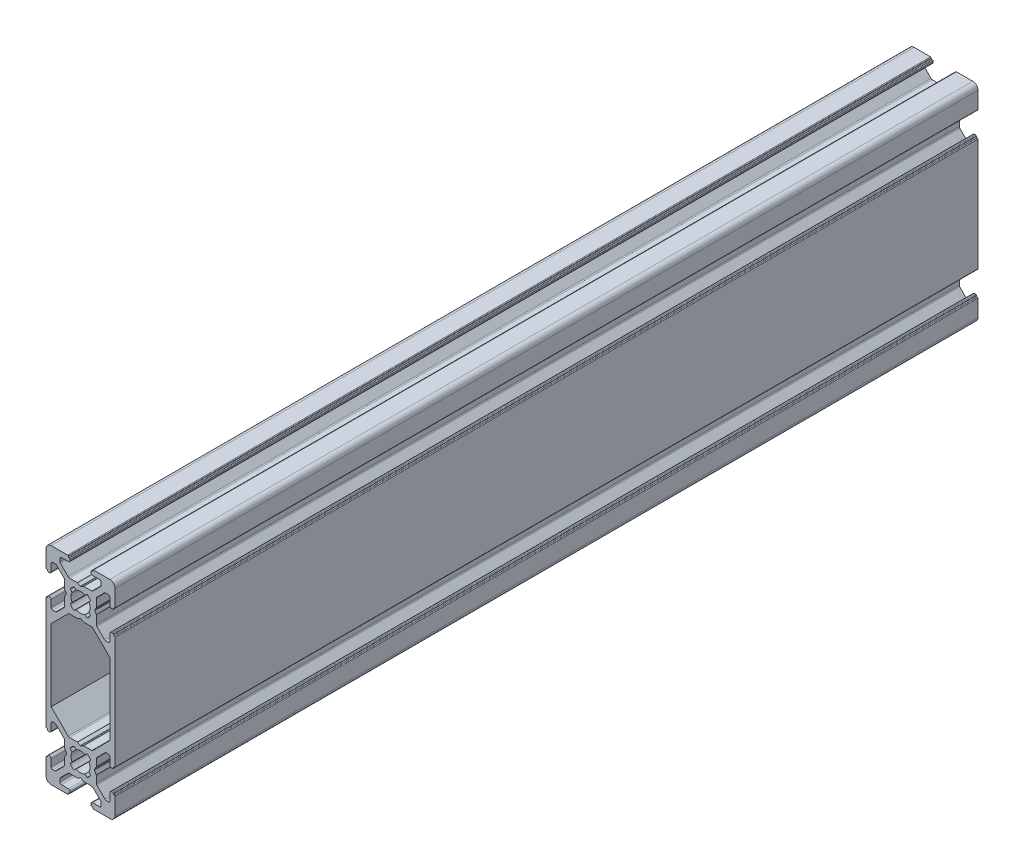
SolidWorks part; units mm, degrees
ref_plane "Front Plane" through (0, 0, 0) normal (0, 0, 1) x (1, 0, 0)
ref_plane "Top Plane" through (0, 0, 0) normal (0, 1, 0) x (1, 0, 0)
ref_plane "Right Plane" through (0, 0, 0) normal (1, 0, 0) x (0, 0, -1)
sketch "Sketch2" plane through (0, 0, 0) normal (0, 0, 1) x (1, 0, 0)
  line L0 (0, -19.2121) -> (0, 56.5718) construction
  line L1 (-10, 36.2558) -> (-10, 8.5)
  line L2 (10, 36.2558) -> (10, 8.5)
  line L3 (-8.5, 30.4451) -> (-8.5, 9.5607)
  line L4 (8.5, 30.4451) -> (8.5, 9.5607)
  line L5 (-3.5858, 4.6464) -> (-8.5, 9.5607)
  line L6 (-4.7214, 3.4608) -> (-7.1142, 5.8536)
  line L7 (-3.75, -10) -> (-8.5, -10)
  line L8 (-4.7214, -3.4608) -> (-7.1142, -5.8536)
  line L9 (-9.7, -3.55) -> (-9.8, -3.55)
  line L10 (-9.5, -3.2) -> (-9.5, -3.35)
  line L11 (-7.4678, -6) -> (-8, -6)
  line L12 (-9, -3) -> (-9.3, -3)
  line L13 (-8.5, -3.5) -> (-8.5, -5.5)
  line L14 (-10, -3.75) -> (-10, -8.5)
  line L15 (-7.4678, 6) -> (-8, 6)
  line L16 (-9.7, 3.55) -> (-9.8, 3.55)
  line L17 (-9.5, 3.2) -> (-9.5, 3.35)
  line L18 (-9, 3) -> (-9.3, 3)
  line L19 (-8.5, 3.5) -> (-8.5, 5.5)
  line L20 (-10, 3.75) -> (-10, 8.5)
  line L21 (-4.575, -3.1072) -> (-4.575, -1.0835)
  line L22 (4.575, -3.1072) -> (4.575, -1.0835)
  line L23 (3.2322, -4.5) -> (0.9536, -4.5)
  line L24 (-3.2322, -4.5) -> (-0.9536, -4.5)
  line L25 (-0.8536, -4.4732) -> (-0.1, -4.0381)
  line L26 (0.8536, -4.4732) -> (0.1, -4.0381)
  line L27 (-3.5, -8.5) -> (-5.5, -8.5)
  line L28 (-3.2, -9.5) -> (-3.35, -9.5)
  line L29 (-3.55, -9.7) -> (-3.55, -9.8)
  line L30 (-6, -7.2678) -> (-6, -8)
  line L31 (-3.5858, -4.6464) -> (-5.8536, -6.9142)
  line L32 (-3, -9) -> (-3, -9.3)
  line L33 (3.55, -9.7) -> (3.55, -9.8)
  line L34 (3.2, -9.5) -> (3.35, -9.5)
  line L35 (6, -7.2678) -> (6, -8)
  line L36 (3, -9) -> (3, -9.3)
  line L37 (3.5, -8.5) -> (5.5, -8.5)
  line L38 (3.75, -10) -> (8.5, -10)
  line L39 (10, -3.7) -> (10, -8.5)
  line L40 (8.5, -3.5) -> (8.5, -5.5)
  line L41 (9.5, -3.2) -> (9.5, -3.3)
  line L42 (9.7, -3.5) -> (9.8, -3.5)
  line L43 (7.4678, -6) -> (8, -6)
  line L44 (4.7214, -3.4608) -> (7.1142, -5.8536)
  line L45 (3.5858, -4.6464) -> (5.8536, -6.9142)
  line L46 (9, -3) -> (9.3, -3)
  line L47 (3.5858, 4.6464) -> (8.5, 9.5607)
  line L48 (3.2322, 4.5) -> (0.9536, 4.5)
  line L49 (-3.2322, 4.5) -> (-0.9536, 4.5)
  line L50 (-0.8536, 4.4732) -> (-0.1, 4.0381)
  line L51 (0.8536, 4.4732) -> (0.1, 4.0381)
  line L52 (1.2582, 2.4453) -> (1.9099, 2.9922)
  line L53 (-4.575, 3.1072) -> (-4.575, 1.0835)
  line L54 (-4.5482, 0.9835) -> (-4.0381, 0.1)
  line L55 (-4.5482, -0.9835) -> (-4.0381, -0.1)
  line L56 (-1.2623, 2.4431) -> (-1.9139, 2.9896)
  line L57 (-2.4453, 1.2582) -> (-2.9922, 1.9099)
  line L58 (-2.4431, -1.2623) -> (-2.9897, -1.9139)
  line L59 (-1.2582, -2.4453) -> (-1.9099, -2.9922)
  line L60 (1.2623, -2.4431) -> (1.9139, -2.9897)
  line L61 (2.4453, 1.2582) -> (2.9896, 1.9139)
  line L62 (4.5482, -0.9835) -> (4.0381, -0.1)
  line L63 (4.5482, 0.9835) -> (4.0381, 0.1)
  line L64 (4.575, 3.1072) -> (4.575, 1.0835)
  line L65 (2.4453, -1.2582) -> (2.9922, -1.9099)
  line L66 (9.7, 3.5) -> (9.8, 3.5)
  line L67 (9.5, 3.2) -> (9.5, 3.3)
  line L68 (7.4678, 6) -> (8, 6)
  line L69 (9, 3) -> (9.3, 3)
  line L70 (8.5, 3.5) -> (8.5, 5.5)
  line L71 (10, 3.7) -> (10, 8.5)
  line L72 (4.7214, 3.4608) -> (7.1142, 5.8536)
  line L73 (-4.7214, 36.345) -> (-6.9142, 34.1522)
  line L74 (-3.5858, 35.3593) -> (-8.5, 30.4451)
  line L75 (-4.7214, 43.6666) -> (-6.9142, 45.8593)
  line L76 (-3.75, 50) -> (-8.5, 50)
  line L77 (-10, 43.6558) -> (-10, 48.5)
  line L78 (-8.5, 43.4558) -> (-8.5, 45.5058)
  line L79 (0, 40.0058) -> (15.2221, 40.0058) construction
  line L80 (-8.5, 36.4558) -> (-8.5, 34.5058)
  line L81 (-9, 36.9558) -> (-9.3, 36.9558)
  line L82 (-7.2678, 34.0058) -> (-8, 34.0058)
  line L83 (-9.5, 36.7558) -> (-9.5, 36.6558)
  line L84 (-9.7, 36.4558) -> (-9.8, 36.4558)
  line L85 (-9, 42.9558) -> (-9.3, 42.9558)
  line L86 (-9.5, 43.1558) -> (-9.5, 43.2558)
  line L87 (-9.7, 43.4558) -> (-9.8, 43.4558)
  line L88 (-7.2678, 46.0058) -> (-8, 46.0058)
  line L89 (4.7214, 43.6666) -> (6.9142, 45.8593)
  line L90 (10, 43.6558) -> (10, 48.5)
  line L91 (8.5, 43.4558) -> (8.5, 45.5058)
  line L92 (3.5858, 35.3593) -> (8.5, 30.4451)
  line L94 (3.2322, 35.5058) -> (0.9536, 35.5058)
  line L95 (1.2582, 37.5605) -> (1.8871, 37.0581)
  line L96 (-1.2582, 37.5605) -> (-1.8871, 37.0581)
  line L97 (-2.4453, 38.7476) -> (-2.9477, 38.1187)
  line L98 (-2.4453, 41.264) -> (-2.9477, 41.8928)
  line L99 (-1.2582, 42.4511) -> (-1.8871, 42.9535)
  line L100 (0.8536, 35.5326) -> (0.1, 35.9677)
  line L101 (-0.8536, 35.5326) -> (-0.1, 35.9677)
  line L102 (-3.2322, 35.5058) -> (-0.9536, 35.5058)
  line L103 (-4.575, 36.6985) -> (-4.575, 39.1772)
  line L104 (-4.5482, 39.2772) -> (-4.142, 39.9808)
  line L105 (-4.5482, 40.8844) -> (-4.142, 40.1808)
  line L106 (-4.575, 43.313) -> (-4.575, 40.9844)
  line L107 (1.2582, 42.4511) -> (1.8871, 42.9535)
  line L108 (9, 42.9558) -> (9.3, 42.9558)
  line L109 (9.5, 43.1558) -> (9.5, 43.2558)
  line L110 (9.7, 43.4558) -> (9.8, 43.4558)
  line L111 (9, 36.9558) -> (9.3, 36.9558)
  line L112 (4.7214, 36.345) -> (6.9142, 34.1522)
  line L113 (7.2678, 34.0058) -> (8, 34.0058)
  line L114 (9.7, 36.4558) -> (9.8, 36.4558)
  line L115 (9.5, 36.7558) -> (9.5, 36.6558)
  line L116 (8.5, 36.4558) -> (8.5, 34.5058)
  line L117 (2.4453, 38.7476) -> (2.9477, 38.1187)
  line L118 (4.575, 43.313) -> (4.575, 40.9844)
  line L119 (4.5482, 40.8844) -> (4.142, 40.1808)
  line L120 (4.5482, 39.2772) -> (4.142, 39.9808)
  line L121 (4.575, 36.6985) -> (4.575, 39.1772)
  line L122 (2.4453, 41.264) -> (2.9477, 41.8928)
  line L123 (3.2322, 44.5) -> (0.9536, 44.5)
  line L124 (-3.55, 49.7) -> (-3.55, 49.8)
  line L125 (-3.2, 49.5) -> (-3.35, 49.5)
  line L126 (-3.5858, 44.6464) -> (-5.8536, 46.9142)
  line L127 (-6, 47.2678) -> (-6, 48)
  line L128 (0.8536, 44.4732) -> (0.0592, 44.0146)
  line L129 (-0.8536, 44.4732) -> (-0.0592, 44.0146)
  line L130 (-3.2322, 44.5) -> (-0.9536, 44.5)
  line L131 (-3, 49) -> (-3, 49.3)
  line L132 (-3.5, 48.5) -> (-5.5, 48.5)
  line L133 (3, 49) -> (3, 49.3)
  line L134 (3.5858, 44.6464) -> (5.8536, 46.9142)
  line L135 (6, 47.2678) -> (6, 48)
  line L136 (3.55, 49.7) -> (3.55, 49.8)
  line L137 (3.2, 49.5) -> (3.35, 49.5)
  line L138 (3.5, 48.5) -> (5.5, 48.5)
  line L139 (3.75, 50) -> (8.5, 50)
  line L140 (-34.2612, 0) -> (36.5039, 0) construction
  line L279 (7.2678, 46.0058) -> (8, 46.0058)
  arc A0 (-5.8536, -6.9142) -> (-6, -7.2678) centre (-5.5, -7.2678) ccw
  arc A1 (-6, -8) -> (-5.5, -8.5) centre (-5.5, -8) ccw
  arc A2 (-8.5, -3.5) -> (-9, -3) centre (-9, -3.5) ccw
  arc A3 (-9.7, -3.55) -> (-9.5, -3.35) centre (-9.7, -3.35) ccw
  arc A4 (-9.8, -3.55) -> (-10, -3.75) centre (-9.8, -3.75) ccw
  arc A5 (-9.3, -3) -> (-9.5, -3.2) centre (-9.3, -3.2) ccw
  arc A6 (-7.4678, -6) -> (-7.1142, -5.8536) centre (-7.4678, -5.5) ccw
  arc A7 (-10, -8.5) -> (-8.5, -10) centre (-8.5, -8.5) ccw
  arc A8 (-8.5, -5.5) -> (-8, -6) centre (-8, -5.5) ccw
  arc A9 (-8, 6) -> (-8.5, 5.5) centre (-8, 5.5) ccw
  arc A10 (-7.1142, 5.8536) -> (-7.4678, 6) centre (-7.4678, 5.5) ccw
  arc A11 (-9.5, 3.35) -> (-9.7, 3.55) centre (-9.7, 3.35) ccw
  arc A12 (-10, 3.75) -> (-9.8, 3.55) centre (-9.8, 3.75) ccw
  arc A13 (-9.5, 3.2) -> (-9.3, 3) centre (-9.3, 3.2) ccw
  arc A14 (-9, 3) -> (-8.5, 3.5) centre (-9, 3.5) ccw
  arc A15 (9, -3) -> (8.5, -3.5) centre (9, -3.5) ccw
  arc A16 (-4.7214, -3.4608) -> (-4.575, -3.1072) centre (-5.075, -3.1072) ccw
  arc A17 (-3.2322, -4.5) -> (-3.5858, -4.6464) centre (-3.2322, -5) ccw
  arc A18 (0.8536, -4.4732) -> (0.9536, -4.5) centre (0.9536, -4.3) ccw
  arc A19 (-0.9536, -4.5) -> (-0.8536, -4.4732) centre (-0.9536, -4.3) ccw
  arc A20 (0.1, -4.0381) -> (-0.1, -4.0381) centre (0, -4.2113) ccw
  arc A21 (-3.2, -9.5) -> (-3, -9.3) centre (-3.2, -9.3) ccw
  arc A22 (-3.75, -10) -> (-3.55, -9.8) centre (-3.75, -9.8) ccw
  arc A23 (-3.35, -9.5) -> (-3.55, -9.7) centre (-3.35, -9.7) ccw
  arc A24 (-3, -9) -> (-3.5, -8.5) centre (-3.5, -9) ccw
  arc A25 (3.5858, -4.6464) -> (3.2322, -4.5) centre (3.2322, -5) ccw
  arc A26 (4.575, -3.1072) -> (4.7214, -3.4608) centre (5.075, -3.1072) ccw
  arc A27 (3.55, -9.7) -> (3.35, -9.5) centre (3.35, -9.7) ccw
  arc A28 (3.55, -9.8) -> (3.75, -10) centre (3.75, -9.8) ccw
  arc A29 (3, -9.3) -> (3.2, -9.5) centre (3.2, -9.3) ccw
  arc A30 (6, -7.2678) -> (5.8536, -6.9142) centre (5.5, -7.2678) ccw
  arc A31 (8.5, -10) -> (10, -8.5) centre (8.5, -8.5) ccw
  arc A32 (5.5, -8.5) -> (6, -8) centre (5.5, -8) ccw
  arc A33 (9.5, -3.2) -> (9.3, -3) centre (9.3, -3.2) ccw
  arc A34 (10, -3.7) -> (9.8, -3.5) centre (9.8, -3.7) ccw
  arc A35 (9.5, -3.3) -> (9.7, -3.5) centre (9.7, -3.3) ccw
  arc A36 (7.1142, -5.8536) -> (7.4678, -6) centre (7.4678, -5.5) ccw
  arc A37 (8, -6) -> (8.5, -5.5) centre (8, -5.5) ccw
  arc A38 (3.5, -8.5) -> (3, -9) centre (3.5, -9) ccw
  arc A39 (2.9896, 1.9139) -> (1.9099, 2.9922) centre (0, 0) ccw
  arc A40 (1.9139, -2.9897) -> (2.9922, -1.9099) centre (0, 0) ccw
  arc A41 (1.2582, 2.4453) -> (-1.2623, 2.4431) centre (0, 0) ccw
  arc A42 (-0.1, 4.0381) -> (0.1, 4.0381) centre (0, 4.2113) ccw
  arc A43 (0.9536, 4.5) -> (0.8536, 4.4732) centre (0.9536, 4.3) ccw
  arc A44 (-0.8536, 4.4732) -> (-0.9536, 4.5) centre (-0.9536, 4.3) ccw
  arc A45 (-3.5858, 4.6464) -> (-3.2322, 4.5) centre (-3.2322, 5) ccw
  arc A46 (-4.575, 3.1072) -> (-4.7214, 3.4608) centre (-5.075, 3.1072) ccw
  arc A47 (-4.5482, -0.9835) -> (-4.575, -1.0835) centre (-4.375, -1.0835) ccw
  arc A48 (-4.575, 1.0835) -> (-4.5482, 0.9835) centre (-4.375, 1.0835) ccw
  arc A49 (-4.0381, -0.1) -> (-4.0381, 0.1) centre (-4.2113, 0) ccw
  arc A50 (-1.9139, 2.9896) -> (-2.9922, 1.9099) centre (0, 0) ccw
  arc A51 (-2.9897, -1.9139) -> (-1.9099, -2.9922) centre (0, 0) ccw
  arc A52 (-2.4453, 1.2582) -> (-2.4431, -1.2623) centre (0, 0) ccw
  arc A53 (-1.2582, -2.4453) -> (1.2623, -2.4431) centre (0, 0) ccw
  arc A54 (3.2322, 4.5) -> (3.5858, 4.6464) centre (3.2322, 5) ccw
  arc A55 (4.7214, 3.4608) -> (4.575, 3.1072) centre (5.075, 3.1072) ccw
  arc A56 (4.5482, 0.9835) -> (4.575, 1.0835) centre (4.375, 1.0835) ccw
  arc A57 (4.575, -1.0835) -> (4.5482, -0.9835) centre (4.375, -1.0835) ccw
  arc A58 (4.0381, 0.1) -> (4.0381, -0.1) centre (4.2113, 0) ccw
  arc A59 (2.4453, -1.2582) -> (2.4453, 1.2582) centre (0, 0) ccw
  arc A60 (9.7, 3.5) -> (9.5, 3.3) centre (9.7, 3.3) ccw
  arc A61 (9.8, 3.5) -> (10, 3.7) centre (9.8, 3.7) ccw
  arc A62 (9.3, 3) -> (9.5, 3.2) centre (9.3, 3.2) ccw
  arc A63 (7.4678, 6) -> (7.1142, 5.8536) centre (7.4678, 5.5) ccw
  arc A64 (8.5, 5.5) -> (8, 6) centre (8, 5.5) ccw
  arc A65 (8.5, 3.5) -> (9, 3) centre (9, 3.5) ccw
  arc A66 (-6, 47.2678) -> (-5.8536, 46.9142) centre (-5.5, 47.2678) ccw
  arc A67 (-5.5, 48.5) -> (-6, 48) centre (-5.5, 48) ccw
  arc A68 (-9, 42.9558) -> (-8.5, 43.4558) centre (-9, 43.4558) ccw
  arc A69 (-8.5, 36.4558) -> (-9, 36.9558) centre (-9, 36.4558) ccw
  arc A70 (-8.5, 34.5058) -> (-8, 34.0058) centre (-8, 34.5058) ccw
  arc A71 (-7.2678, 34.0058) -> (-6.9142, 34.1522) centre (-7.2678, 34.5058) ccw
  arc A72 (-9.3, 36.9558) -> (-9.5, 36.7558) centre (-9.3, 36.7558) ccw
  arc A73 (-9.8, 36.4558) -> (-10, 36.2558) centre (-9.8, 36.2558) ccw
  arc A74 (-9.7, 36.4558) -> (-9.5, 36.6558) centre (-9.7, 36.6558) ccw
  arc A75 (-9.5, 43.1558) -> (-9.3, 42.9558) centre (-9.3, 43.1558) ccw
  arc A76 (-10, 43.6558) -> (-9.8, 43.4558) centre (-9.8, 43.6558) ccw
  arc A77 (-9.5, 43.2558) -> (-9.7, 43.4558) centre (-9.7, 43.2558) ccw
  arc A78 (-6.9142, 45.8593) -> (-7.2678, 46.0058) centre (-7.2678, 45.5058) ccw
  arc A79 (-8, 46.0058) -> (-8.5, 45.5058) centre (-8, 45.5058) ccw
  arc A80 (-8.5, 50) -> (-10, 48.5) centre (-8.5, 48.5) ccw
  arc A81 (1.8871, 37.0581) -> (2.9477, 38.1187) centre (0, 40.0058) ccw
  arc A82 (2.9477, 41.8928) -> (1.8871, 42.9535) centre (0, 40.0058) ccw
  arc A83 (-1.2582, 37.5605) -> (1.2582, 37.5605) centre (0, 40.0058) ccw
  arc A84 (-2.4453, 41.264) -> (-2.4453, 38.7476) centre (0, 40.0058) ccw
  arc A85 (-2.9477, 38.1187) -> (-1.8871, 37.0581) centre (0, 40.0058) ccw
  arc A86 (-1.8871, 42.9535) -> (-2.9477, 41.8928) centre (0, 40.0058) ccw
  arc A87 (0.1, 35.9677) -> (-0.1, 35.9677) centre (0, 35.7945) ccw
  arc A88 (-0.9536, 35.5058) -> (-0.8536, 35.5326) centre (-0.9536, 35.7058) ccw
  arc A89 (0.8536, 35.5326) -> (0.9536, 35.5058) centre (0.9536, 35.7058) ccw
  arc A90 (-3.2322, 35.5058) -> (-3.5858, 35.3593) centre (-3.2322, 35.0058) ccw
  arc A91 (-4.142, 39.9808) -> (-4.142, 40.1808) centre (-4.3152, 40.0808) ccw
  arc A92 (-4.575, 40.9844) -> (-4.5482, 40.8844) centre (-4.375, 40.9844) ccw
  arc A93 (-4.5482, 39.2772) -> (-4.575, 39.1772) centre (-4.375, 39.1772) ccw
  arc A94 (-4.575, 43.313) -> (-4.7214, 43.6666) centre (-5.075, 43.313) ccw
  arc A95 (-4.7214, 36.345) -> (-4.575, 36.6985) centre (-5.075, 36.6985) ccw
  arc A96 (1.2582, 42.4511) -> (-1.2582, 42.4511) centre (0, 40.0058) ccw
  arc A97 (9, 36.9558) -> (8.5, 36.4558) centre (9, 36.4558) ccw
  arc A98 (8.5, 43.4558) -> (9, 42.9558) centre (9, 43.4558) ccw
  arc A99 (9.3, 42.9558) -> (9.5, 43.1558) centre (9.3, 43.1558) ccw
  arc A100 (9.8, 43.4558) -> (10, 43.6558) centre (9.8, 43.6558) ccw
  arc A101 (9.7, 43.4558) -> (9.5, 43.2558) centre (9.7, 43.2558) ccw
  arc A102 (8, 34.0058) -> (8.5, 34.5058) centre (8, 34.5058) ccw
  arc A103 (6.9142, 34.1522) -> (7.2678, 34.0058) centre (7.2678, 34.5058) ccw
  arc A104 (9.5, 36.6558) -> (9.7, 36.4558) centre (9.7, 36.6558) ccw
  arc A105 (10, 36.2558) -> (9.8, 36.4558) centre (9.8, 36.2558) ccw
  arc A106 (9.5, 36.7558) -> (9.3, 36.9558) centre (9.3, 36.7558) ccw
  arc A107 (2.4453, 38.7476) -> (2.4453, 41.264) centre (0, 40.0058) ccw
  arc A108 (4.142, 40.1808) -> (4.142, 39.9808) centre (4.3152, 40.0808) ccw
  arc A109 (4.575, 39.1772) -> (4.5482, 39.2772) centre (4.375, 39.1772) ccw
  arc A110 (4.5482, 40.8844) -> (4.575, 40.9844) centre (4.375, 40.9844) ccw
  arc A111 (4.575, 36.6985) -> (4.7214, 36.345) centre (5.075, 36.6985) ccw
  arc A112 (4.7214, 43.6666) -> (4.575, 43.313) centre (5.075, 43.313) ccw
  arc A113 (3.5858, 35.3593) -> (3.2322, 35.5058) centre (3.2322, 35.0058) ccw
  arc A114 (-3.5, 48.5) -> (-3, 49) centre (-3.5, 49) ccw
  arc A115 (-3.55, 49.7) -> (-3.35, 49.5) centre (-3.35, 49.7) ccw
  arc A116 (-3.55, 49.8) -> (-3.75, 50) centre (-3.75, 49.8) ccw
  arc A117 (-3, 49.3) -> (-3.2, 49.5) centre (-3.2, 49.3) ccw
  arc A118 (-3.5858, 44.6464) -> (-3.2322, 44.5) centre (-3.2322, 45) ccw
  arc A119 (-0.8536, 44.4732) -> (-0.9536, 44.5) centre (-0.9536, 44.3) ccw
  arc A120 (0.9536, 44.5) -> (0.8536, 44.4732) centre (0.9536, 44.3) ccw
  arc A121 (-0.0592, 44.0146) -> (0.0592, 44.0146) centre (0, 44.1171) ccw
  arc A122 (3, 49) -> (3.5, 48.5) centre (3.5, 49) ccw
  arc A123 (6, 48) -> (5.5, 48.5) centre (5.5, 48) ccw
  arc A124 (5.8536, 46.9142) -> (6, 47.2678) centre (5.5, 47.2678) ccw
  arc A125 (3.35, 49.5) -> (3.55, 49.7) centre (3.35, 49.7) ccw
  arc A126 (3.75, 50) -> (3.55, 49.8) centre (3.75, 49.8) ccw
  arc A127 (3.2, 49.5) -> (3, 49.3) centre (3.2, 49.3) ccw
  arc A128 (8.5, 45.5058) -> (8, 46.0058) centre (8, 45.5058) ccw
  arc A129 (10, 48.5) -> (8.5, 50) centre (8.5, 48.5) ccw
  arc A130 (7.2678, 46.0058) -> (6.9142, 45.8593) centre (7.2678, 45.5058) ccw
  arc A131 (3.2322, 44.5) -> (3.5858, 44.6464) centre (3.2322, 45) ccw
  dimension "D3" = 5.5
  dimension "D6" = 5.5
  dimension "D1" = 60
  dimension "D2" = 20
  dimension "D4" = 6
  dimension "D5" = 6
  dimension "D7" = 12
  dimension "D8" = 12
  dimension "D9" = 12
  dimension "D10" = 12
  dimension "D11" = 12
  dimension "D12" = 12
extrude "Extrude1" add sketch "Sketch2" along normal blind 250
